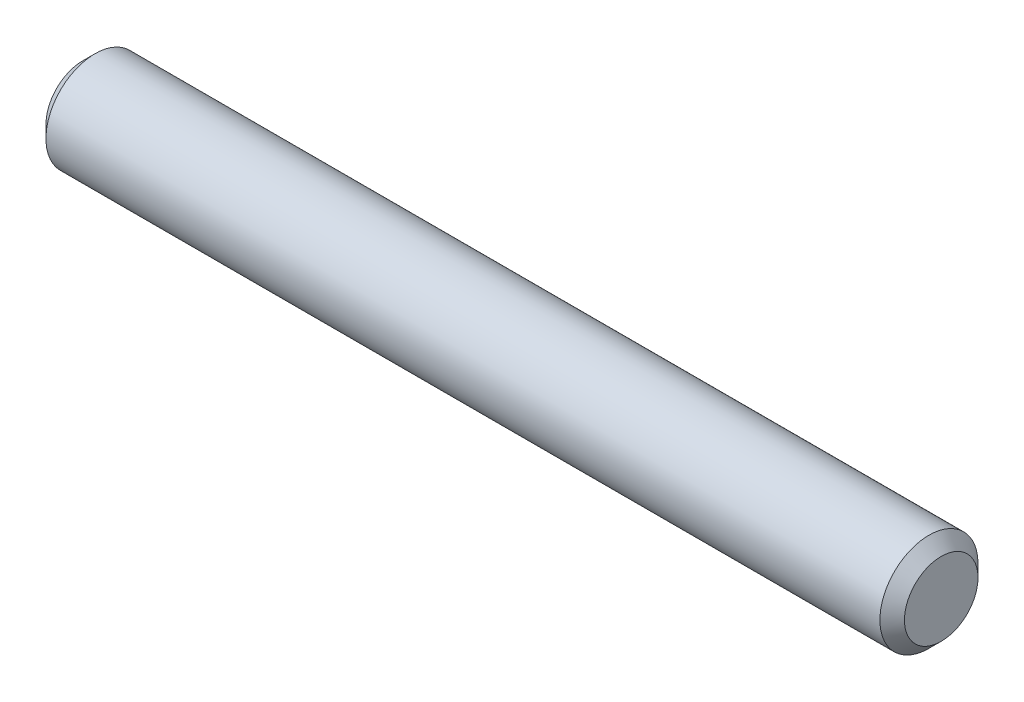
SolidWorks part; units mm, degrees
ref_plane "Piano frontale" through (0, 0, 0) normal (0, 0, 1) x (1, 0, 0)
ref_plane "Piano superiore" through (0, 0, 0) normal (0, 1, 0) x (1, 0, 0)
ref_plane "Piano destro" through (0, 0, 0) normal (1, 0, 0) x (0, 0, -1)
sketch "Schizzo1" plane through (0, 0, 0) normal (1, 0, 0) x (0, 0, -1)
  circle A0 centre (0, 0) radius 4
  dimension "D1" = 8
extrude "Estrusione-Estrusione1" add sketch "Schizzo1" along normal blind 70
chamfer "Smusso1" distance 1 angle 45 2 edges at (70, 0, -4) (0, 0, -4)
